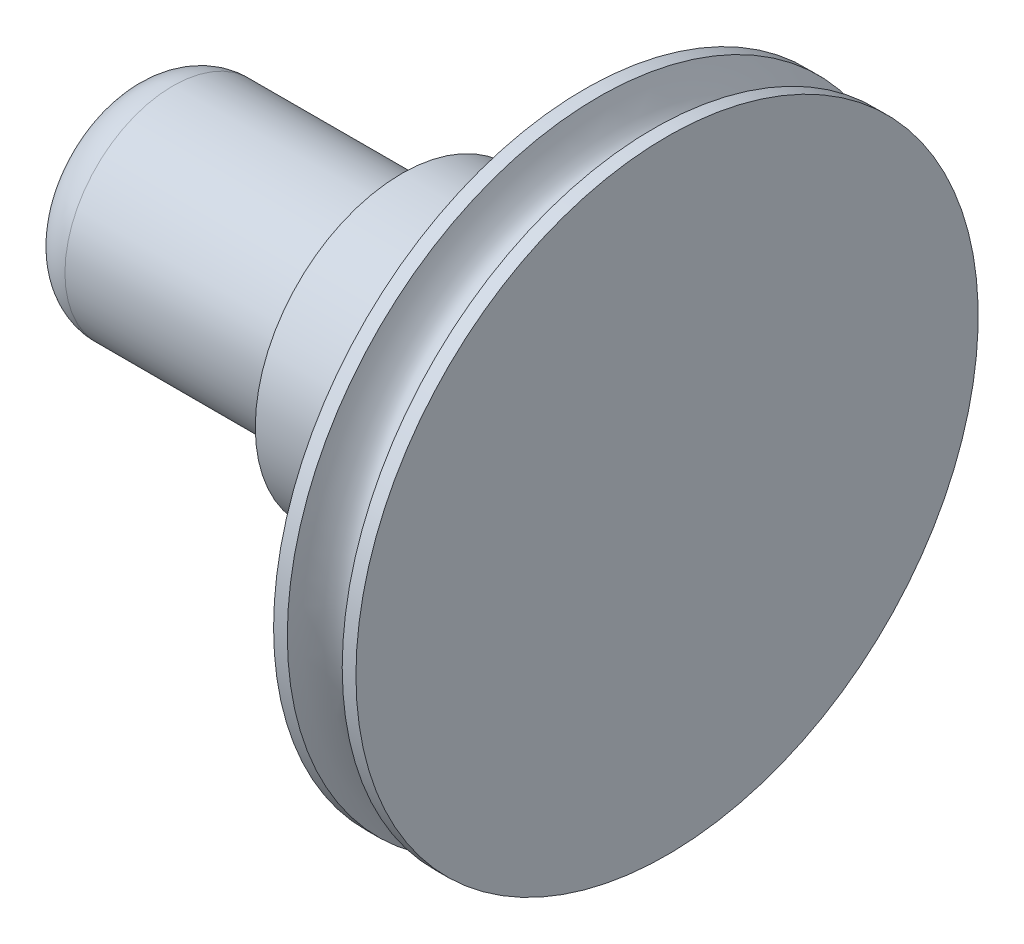
SolidWorks part; units mm, degrees
ref_plane "Front Plane" through (0, 0, 0) normal (0, 0, 1) x (1, 0, 0)
ref_plane "Top Plane" through (0, 0, 0) normal (0, 1, 0) x (1, 0, 0)
ref_plane "Right Plane" through (0, 0, 0) normal (1, 0, 0) x (0, 0, -1)
sketch "Sketch1" plane through (0, 0, 0) normal (0, 1, 0) x (1, 0, 0)
  line L0 (0, 0) -> (4.5, 0)
  line L2 (0, 0) -> (0, 17)
  line L4 (0, 17) -> (0.75, 17)
  line L5 (3.75, 17) -> (4.5, 17)
  line L6 (4.5, 17) -> (4.5, 0)
  spline S0 degree 2 poles (0.75, 17) (2.314, 12.9994) (3.75, 17) knots 0 0 0 1 1 1
  dimension "D1" = 4.5
  dimension "D5" = 3
  dimension "D6" = 0.75
  dimension "D7" = 0.75
revolve "Revolve1" add sketch "Sketch1" angle 360 about L0
sketch "Sketch2" plane through (0, 0, 0) normal (0, 1, 0) x (1, 0, 0)
  line L0 (0, 8) -> (-6.8123, 8)
  line L1 (-6.8123, 8) -> (-10, 8)
  line L3 (-10, 8) -> (-10, 5.9)
  line L4 (-10, 5.9) -> (-25, 5.9)
  line L5 (-25, 5.9) -> (-25, 0)
  line L6 (-25, 0) -> (0, 0)
  line L7 (0, 0) -> (0, 8)
  line L8 (0, 17) -> (0, -17) construction
  point P3 (-10, 6.95)
  point P11 (0, 0)
  point P12 (-6.0238, 9.4303)
  point P13 (-5.3417, 10.1859)
  point P14 (-7.2276, 7.6093)
  point P15 (0, 0)
  point P16 (0, 0)
  point P17 (0, 0)
  dimension "D1" = 0
  dimension "D2" = 5.9
  dimension "D3" = 0
  dimension "D4" = 8
  dimension "D5" = 15
  dimension "D6" = 10
revolve "Revolve2" add sketch "Sketch2" angle 360 about L6
fillet "Fillet1" radius 2.5 1 edges at (-25, 0, 5.9)
